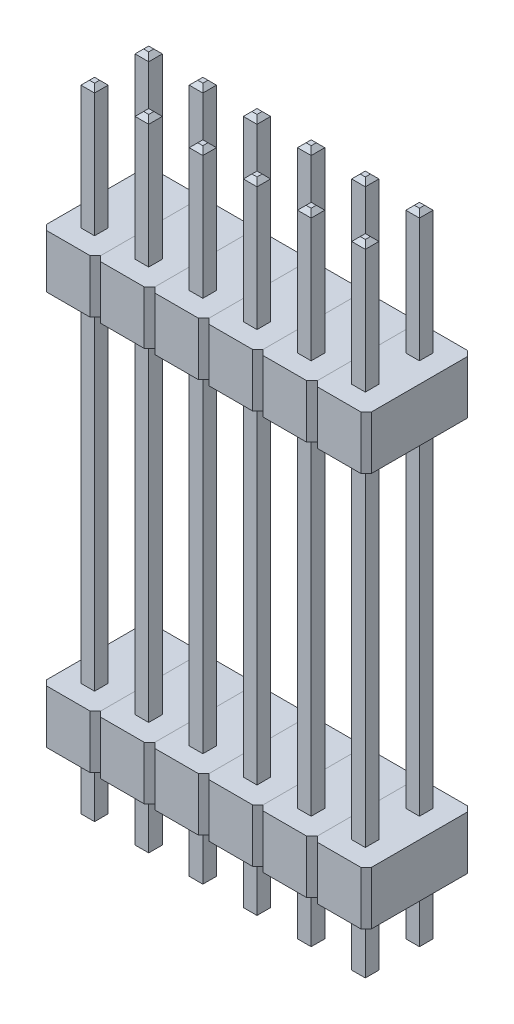
SolidWorks part; units mm, degrees
ref_plane "Спереди" through (0, 0, 0) normal (0, 0, 1) x (1, 0, 0)
ref_plane "Сверху" through (0, 0, 0) normal (0, 1, 0) x (1, 0, 0)
ref_plane "Справа" through (0, 0, 0) normal (1, 0, 0) x (0, 0, -1)
sketch "Эскиз1" plane through (0, 0, 0) normal (0, 1, 0) x (1, 0, 0)
  line L0 (-1.27, 0.98) -> (-1.02, 1.23)
  line L1 (-1.02, 1.23) -> (1.02, 1.23)
  line L2 (1.02, 1.23) -> (1.27, 0.98)
  line L3 (1.27, 0.98) -> (1.27, -3.52)
  line L4 (1.27, -3.52) -> (1.02, -3.77)
  line L5 (1.02, -3.77) -> (-1.02, -3.77)
  line L6 (-1.02, -3.77) -> (-1.27, -3.52)
  line L7 (-1.27, -3.52) -> (-1.27, 0.98)
  point P4 (-0.5185, -3.75)
  dimension "D1" = 2.54
  dimension "D2" = 5
  dimension "D3" = 45
  dimension "D4" = 1.27
  dimension "D5" = 1.23
  dimension "D6" = 0.25
extrude "Бобышка-Вытянуть1" add sketch "Эскиз1" along normal blind 2.5
pattern_linear "Линейный массив1" count 2 spacing 18.5 along (0, 1, 0) of bodies 101
sketch "Эскиз2" plane through (0, 0, 0) normal (0, -1, 0) x (1, 0, 0)
  line L1 (-0.32, 0.32) -> (0.32, 0.32)
  line L2 (-0.32, 0.32) -> (-0.32, -0.32)
  line L3 (-0.32, -0.32) -> (0.32, -0.32)
  line L4 (0.32, 0.32) -> (0.32, -0.32)
  point P4 (0, 0.32)
  point P8 (0.32, 0)
  dimension "D1" = 0.64
extrude "Бобышка-Вытянуть2" add sketch "Эскиз2" along normal blind 3 and the other way blind 27 separate body
chamfer "Фаска1" distance 0.2 angle 45 8 edges at (0, -3, 0.32) (0.32, -3, 0) (0, -3, -0.32) (-0.32, -3, 0) (0, 27, -0.32) (0.32, 27, 0) (0, 27, 0.32) (-0.32, 27, 0)
pattern_linear "Линейный массив2" count 2 spacing 2.54 along (0, 0, 1) of "Бобышка-Вытянуть2"
pattern_linear "Линейный массив3" count 6 spacing 2.54 along (1, 0, 0) of bodies 101 102 104 103
equation "\"D4@Эскиз1\"=\"D1@Эскиз1\"/2"
equation "\"D5@Эскиз1\"=(\"D2@Эскиз1\"-2.54)/2"
